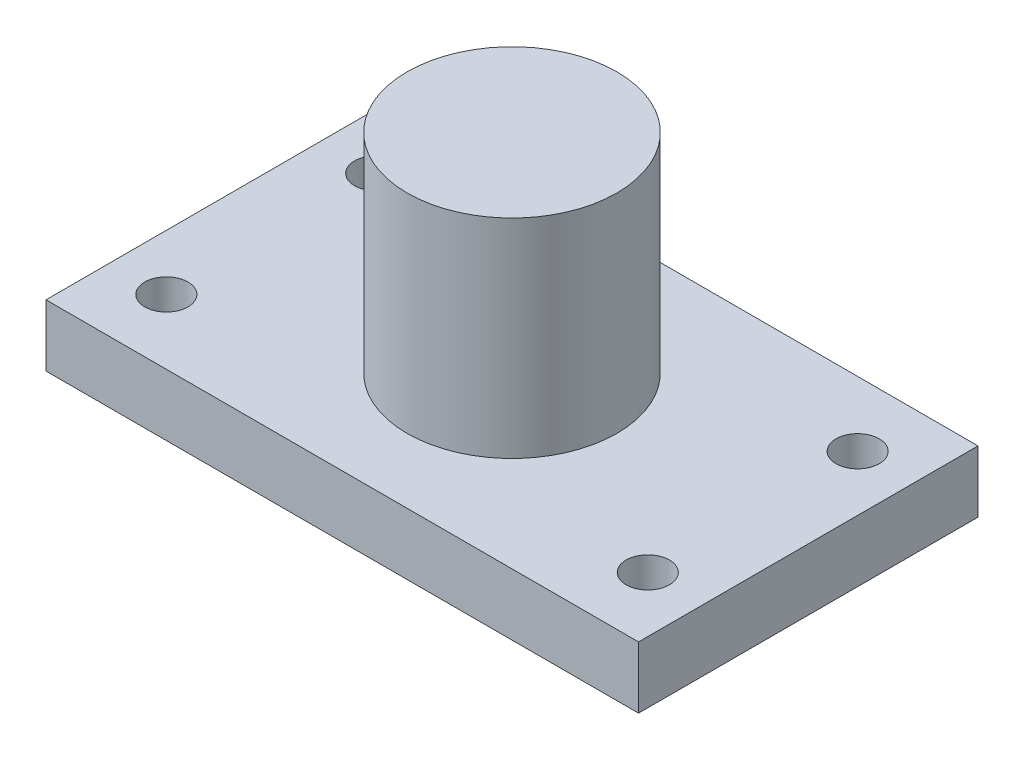
SolidWorks part; units mm, degrees
ref_plane "前视基准面" through (0, 0, 0) normal (0, 0, 1) x (1, 0, 0)
ref_plane "上视基准面" through (0, 0, 0) normal (0, 1, 0) x (1, 0, 0)
ref_plane "右视基准面" through (0, 0, 0) normal (1, 0, 0) x (0, 0, -1)
sketch "草图1" plane through (0, 0, 0) normal (0, 1, 0) x (1, 0, 0)
  line L1 (0, 0) -> (48, 0)
  line L2 (0, 0) -> (0, -27.5)
  line L3 (0, -27.5) -> (48, -27.5)
  line L4 (48, 0) -> (48, -27.5)
  dimension "D1" = 48
  dimension "D2" = 27.5
extrude "凸台-拉伸1" add sketch "草图1" along normal blind 5
sketch "草图2" plane through (0, 5, 0) normal (0, 1, 0) x (1, 0, 0)
  line L0 (48, 0) -> (0, -27.5) construction
  circle A0 centre (24, -13.75) radius 8.5
  dimension "D1" = 17
extrude "凸台-拉伸2" add sketch "草图2" along normal blind 16.87
sketch "草图3" plane through (0, 0, 0) normal (0, -1, 0) x (1, 0, 0)
  line L0 (0, 27.5) -> (48, 0) construction
  line L1 (48, 0) -> (24, 13.75) construction
  line L2 (24, 13.75) -> (44.5212, 13.75) construction
  line L3 (24, 13.75) -> (24, 19.3377) construction
  circle A0 centre (4.5, 22.25) radius 1.75
  circle A1 centre (43.5, 22.25) radius 1.75
  circle A2 centre (43.5, 5.25) radius 1.75
  circle A3 centre (4.5, 5.25) radius 1.75
  dimension "D1" = 17
  dimension "D2" = 39
  dimension "D3" = 3.5
extrude "切除-拉伸1" cut sketch "草图3" against normal through all both and the other way through all
